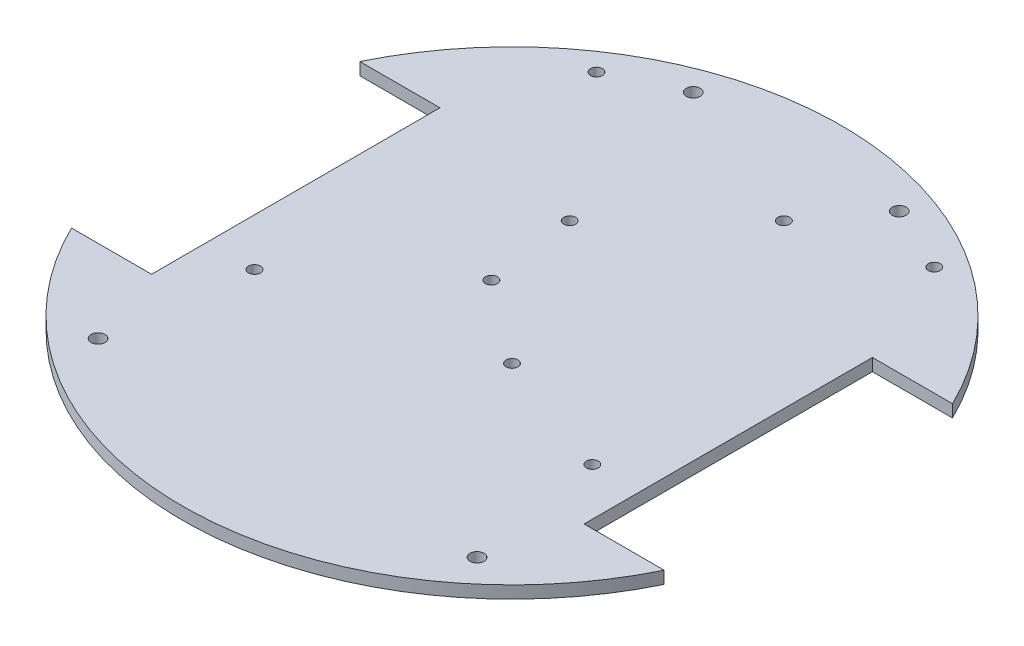
SolidWorks part; units mm, degrees
ref_plane "Plan de face" through (0, 0, 0) normal (0, 0, 1) x (1, 0, 0)
ref_plane "Plan de dessus" through (0, 0, 0) normal (0, 1, 0) x (1, 0, 0)
ref_plane "Plan de droite" through (0, 0, 0) normal (1, 0, 0) x (0, 0, -1)
sketch "Esquisse1" plane through (0, 0, 0) normal (0, 1, 0) x (1, 0, 0)
  circle A0 centre (0, 0) radius 80
  dimension "D1" = 160
extrude "Boss.-Extru.1" add sketch "Esquisse1" along normal blind 3
sketch "Esquisse2" plane through (0, 3, 0) normal (0, 1, 0) x (1, 0, 0)
  line L0 (0, -91.4679) -> (0, 85.097) construction
  line L1 (-107.5, -35) -> (-52.5, -35)
  line L2 (-107.5, -35) -> (-107.5, 35)
  line L3 (-107.5, 35) -> (-52.5, 35)
  line L4 (-52.5, -35) -> (-52.5, 35)
  line L5 (-107.5, -35) -> (-52.5, 35) construction
  line L6 (-107.5, 35) -> (-52.5, -35) construction
  line L7 (107.5, -35) -> (52.5, -35)
  line L8 (52.5, -35) -> (52.5, 35)
  line L9 (107.5, 35) -> (52.5, 35)
  line L10 (107.5, -35) -> (107.5, 35)
  circle A0 centre (0, 0) radius 80 construction
  point P0 (-80, 0)
  point P14 (0, 0)
  dimension "D1" = 70
  dimension "D2" = 55
extrude "Enlèv. mat.-Extru.1" cut sketch "Esquisse2" against normal through all
sketch "supports moteurs" plane through (0, 3, 0) normal (0, 1, 0) x (1, 0, 0)
  line L0 (-88.0211, 0) -> (120.7529, 0) construction
  line L1 (0, -36.8171) -> (0, 105.1916) construction
  line L2 (-48.5, -25) -> (-33.5, -25)
  line L3 (-48.5, -25) -> (-48.5, 65)
  line L4 (-48.5, 65) -> (-33.5, 65)
  line L5 (-33.5, -25) -> (-33.5, 65)
  line L6 (48.5, -25) -> (33.5, -25)
  line L7 (33.5, -25) -> (33.5, 65)
  line L8 (48.5, -25) -> (48.5, 65)
  line L9 (48.5, 65) -> (33.5, 65)
  line L10 (-52.5, -35) -> (-52.5, 35) construction
  dimension "D1" = 15
  dimension "D2" = 90
  dimension "D3" = 65
  dimension "D4" = 4
hole_wizard "Dégagement M2.51" positions "Esquisse5" profile "Esquisse4" hole size "M2.5" standard "Iso"
sketch "Esquisse5" plane through (0, 3, 0) normal (0, 1, 0) x (1, 0, 0)
  line L0 (-48.5, 65) -> (-33.5, 65) construction
  line L1 (-48.5, -25) -> (-33.5, -25) construction
  line L3 (-41, -25) -> (-41, 65) construction
  line L5 (41, 65) -> (41, -25) construction
  line L6 (48.5, 65) -> (33.5, 65) construction
  line L7 (48.5, -25) -> (33.5, -25) construction
  point P0 (-41, 61.5)
  point P2 (-41, -21.5)
  point P4 (41, -21.5)
  point P6 (41, 61.5)
  dimension "D1" = 3.5
  dimension "D2" = 3.5
sketch "Esquisse4" plane through (-41, 3, -61.5) normal (1, 0, 0) x (0, 0, 1)
  line L0 (0, 0) -> (0, 24.8712)
  line L1 (0, 24.8712) -> (1.45, 24)
  line L2 (1.45, 24) -> (1.45, 0)
  line L5 (1.45, 0) -> (0, 0)
  line L10 (0, 24.8712) -> (-1.45, 24) construction
  line L11 (0, -6.35) -> (0, 107.95) construction
  dimension "Diamètre du perçage" = 2.9
  dimension "Profondeur du perçage" = 24
  dimension "Angle de pointe" = 118
sketch "composants" plane through (0, 3, 0) normal (0, 1, 0) x (1, 0, 0)
  line L0 (0, -36.8171) -> (0, 105.1916) construction
  line L1 (-25, 65) -> (25, 65)
  line L2 (-25, 65) -> (-25, 15)
  line L3 (-25, 15) -> (25, 15)
  line L4 (25, 65) -> (25, 15)
  line L5 (13, 65) -> (13, 53) construction
  line L6 (-25, -15) -> (25, -15)
  line L7 (-25, -15) -> (-25, 10)
  line L8 (-25, 10) -> (25, 10)
  line L9 (25, -15) -> (25, 10)
  line L10 (-27.5, -20) -> (27.5, -20)
  line L11 (-27.5, -20) -> (-27.5, -65)
  line L12 (-27.5, -65) -> (27.5, -65)
  line L13 (27.5, -20) -> (27.5, -65)
  line L14 (13, 53) -> (25, 53) construction
  line L15 (-25, 27) -> (-13, 27) construction
  line L16 (-13, 27) -> (-13, 15) construction
  line L17 (-25, 10) -> (25, -15) construction
  line L18 (-25, -15) -> (25, 10) construction
  line L19 (25, -10) -> (10, -10) construction
  line L20 (10, -10) -> (10, -15) construction
  line L21 (-25, 5) -> (-10, 5) construction
  line L22 (-10, 5) -> (-10, 10) construction
  line L23 (-88.0211, 0) -> (120.7529, 0) construction
  point P4 (0, 65)
  point P15 (0, -20)
  point P28 (0, -2.5)
  dimension "D1" = 50
  dimension "D2" = 50
  dimension "D3" = 25
  dimension "D4" = 5
  dimension "D5" = 55
  dimension "D6" = 45
  dimension "D7" = 5
  dimension "D8" = 12
  dimension "D9" = 12
  dimension "D10" = 12
  dimension "D11" = 12
  dimension "D12" = 50
  dimension "D13" = 15
  dimension "D14" = 5
  dimension "D15" = 15
  dimension "D16" = 5
  dimension "D17" = 2.5
hole_wizard "Dégagement M2.52" positions "Esquisse8" profile "Esquisse7" hole size "M2.5" standard "Iso"
sketch "Esquisse8" plane through (0, 3, 0) normal (0, 1, 0) x (1, 0, 0)
  point P0 (-13, 27)
  point P3 (13, 53)
  point P6 (-10, 5)
  point P9 (10, -10)
sketch "Esquisse7" plane through (-13, 3, -27) normal (1, 0, 0) x (0, 0, 1)
  line L0 (0, 0) -> (0, 24.8712)
  line L1 (0, 24.8712) -> (1.45, 24)
  line L2 (1.45, 24) -> (1.45, 0)
  line L5 (1.45, 0) -> (0, 0)
  line L10 (0, 24.8712) -> (-1.45, 24) construction
  line L11 (0, -6.35) -> (0, 107.95) construction
  dimension "Diamètre du perçage" = 2.9
  dimension "Profondeur du perçage" = 24
  dimension "Angle de pointe" = 118
hole_wizard "Dégagement M31" positions "Esquisse10" profile "Esquisse9" hole size "M3" standard "Iso"
sketch "Esquisse10" plane through (0, 3, 0) normal (0, 1, 0) x (1, 0, 0)
  line L1 (-45.4836, -55) -> (0.5164, -55) construction
  line L2 (0.5164, -55) -> (46.5164, -55) construction
  line L6 (-25, 65) -> (25, 65) construction
  line L7 (-71.9375, -35) -> (-52.5, -35) construction
  point P4 (-45.4836, -55)
  point P6 (46.5164, -55)
  point P14 (-25, 69)
  point P16 (25, 69)
  dimension "D1" = 92
  dimension "D2" = 4
  dimension "D3" = 20
sketch "Esquisse9" plane through (-45.4836, 3, 55) normal (1, 0, 0) x (0, 0, 1)
  line L0 (0, 0) -> (0, 25.0215)
  line L1 (0, 25.0215) -> (1.7, 24)
  line L2 (1.7, 24) -> (1.7, 0)
  line L5 (1.7, 0) -> (0, 0)
  line L10 (0, 25.0215) -> (-1.7, 24) construction
  line L11 (0, -6.35) -> (0, 107.95) construction
  dimension "Diamètre du perçage" = 3.4
  dimension "Profondeur du perçage" = 24
  dimension "Angle de pointe" = 118
